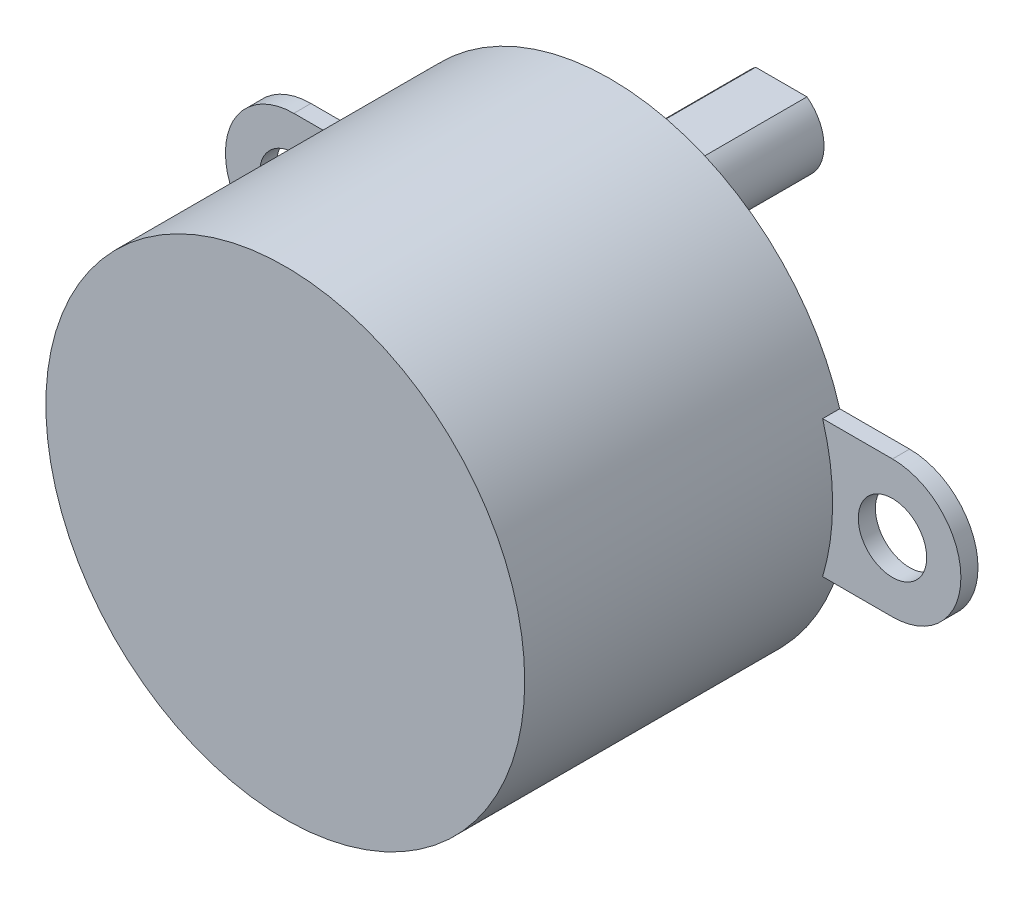
SolidWorks part; units mm, degrees
ref_plane "前视基准面" through (0, 0, 0) normal (0, 0, 1) x (1, 0, 0)
ref_plane "上视基准面" through (0, 0, 0) normal (0, 1, 0) x (1, 0, 0)
ref_plane "右视基准面" through (0, 0, 0) normal (1, 0, 0) x (0, 0, -1)
sketch "草图1" plane through (0, 0, 0) normal (0, 0, 1) x (1, 0, 0)
  circle A0 centre (0, 0) radius 14
  dimension "D1" = 28
extrude "凸台-拉伸1" add sketch "草图1" along normal blind 19
sketch "草图3" plane through (0, 0, 0) normal (0, 0, 1) x (1, 0, 0)
  line L0 (0, 0) -> (0, 14) construction
  circle A0 centre (0, 0) radius 14 construction
  circle A1 centre (0, 6.8352) radius 4
  dimension "D1" = 8
extrude "凸台-拉伸2" add sketch "草图3" against normal blind 1.8
sketch "草图4" plane through (0, 0, -1.8) normal (0, 0, -1) x (-1, 0, 0)
  circle A0 centre (0, 6.8352) radius 2.5
  dimension "D1" = 5
extrude "凸台-拉伸3" add sketch "草图4" along normal blind 8.2
sketch "草图5" plane through (0, 0, 0) normal (0, 0, -1) x (-1, 0, 0)
  line L0 (-17.5, 0) -> (17.5, 0) construction
  line L1 (-17.5, 0) -> (17.5, 0) construction
  line L2 (-17.5, 4) -> (17.5, 4)
  line L3 (-17.5, -4) -> (17.5, -4)
  circle A0 centre (17.5, 0) radius 2
  circle A1 centre (-17.5, 0) radius 2
  arc A2 (-17.5, 4) -> (-17.5, -4) centre (-17.5, 0) ccw
  arc A3 (17.5, -4) -> (17.5, 4) centre (17.5, 0) ccw
  point P4 (0, 0)
  point P7 (0, 0)
  dimension "D2" = 4
  dimension "D3" = 4
  dimension "D4" = 4
  dimension "D1" = 35
extrude "凸台-拉伸4" add sketch "草图5" against normal blind 1
sketch "草图6" plane through (0, 0, -10) normal (0, 0, -1) x (-1, 0, 0)
  line L0 (0, 4.8352) -> (0, 8.8352) construction
  line L1 (-1.5, 8.8352) -> (1.5, 8.8352)
  line L2 (1.5, 4.8352) -> (-1.5, 4.8352)
  arc A0 (1.5, 8.8352) -> (-1.5, 8.8352) centre (0, 6.8352) ccw
  arc A1 (-1.5, 4.8352) -> (1.5, 4.8352) centre (0, 6.8352) ccw
  circle A2 centre (0, 6.8352) radius 2.5 construction
  point P6 (0, 6.8352)
  point P10 (0, 8.8352)
  point P12 (0, 4.8352)
  dimension "D2" = 2.5
  dimension "D1" = 4
extrude "切除-拉伸1" cut sketch "草图6" against normal up to surface (8.2 mm away) up to face at (-2.5, 6.8352, -1.8)
